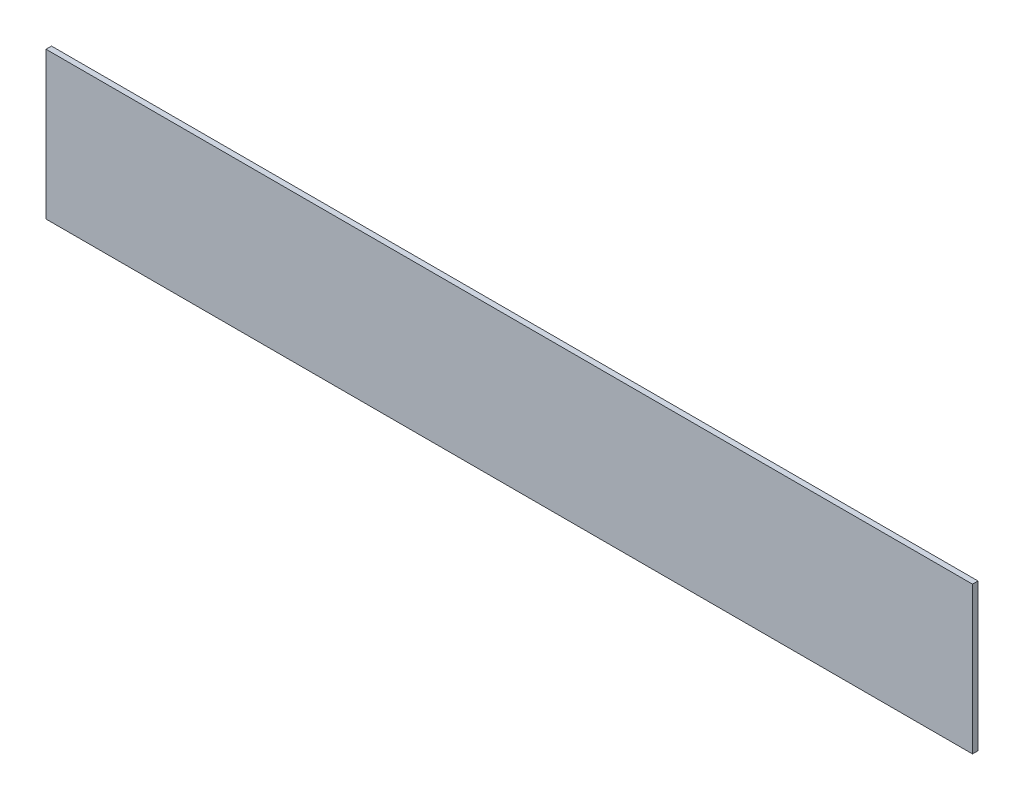
SolidWorks part; units mm, degrees
ref_plane "Přední rovina" through (0, 0, 0) normal (0, 0, 1) x (1, 0, 0)
ref_plane "Horní rovina" through (0, 0, 0) normal (0, 1, 0) x (1, 0, 0)
ref_plane "Pravá rovina" through (0, 0, 0) normal (1, 0, 0) x (0, 0, -1)
sketch "Skica1" plane through (0, 0, 0) normal (0, 0, 1) x (1, 0, 0)
  line L1 (-252, 40) -> (252, 40)
  line L2 (-252, 40) -> (-252, -40)
  line L3 (-252, -40) -> (252, -40)
  line L4 (252, 40) -> (252, -40)
  line L5 (-252, 40) -> (252, -40) construction
  line L6 (-252, -40) -> (252, 40) construction
  point P0 (0, 0)
  dimension "D1" = 504
  dimension "D2" = 80
extrude "Přidat vysunutím1" add sketch "Skica1" along normal blind 3
